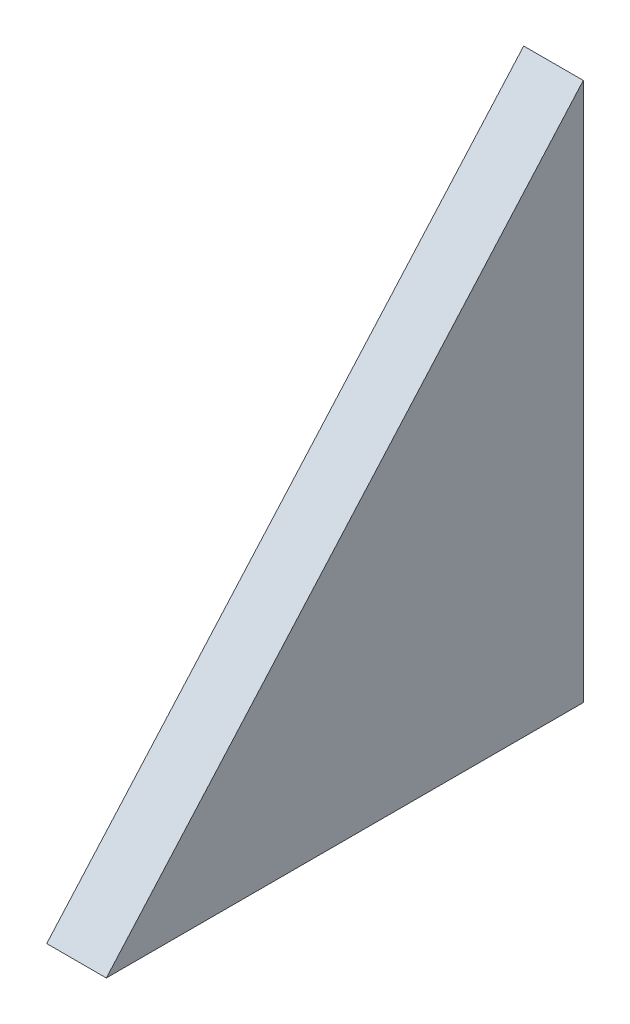
SolidWorks part; units mm, degrees
ref_plane "Alzado" through (0, 0, 0) normal (0, 0, 1) x (1, 0, 0)
ref_plane "Planta" through (0, 0, 0) normal (0, 1, 0) x (1, 0, 0)
ref_plane "Vista lateral" through (0, 0, 0) normal (1, 0, 0) x (0, 0, -1)
sketch "Croquis1" plane through (0, 0, 0) normal (1, 0, 0) x (0, 0, -1)
  line L1 (-32.0744, -36.234) -> (31.9256, -36.234)
  line L4 (31.9256, -36.234) -> (31.9256, 36.066)
  line L5 (-32.0744, -36.234) -> (31.9256, 36.066) construction
  line L6 (0, 0) -> (31.9256, -36.234) construction
  line L9 (-32.0744, -36.234) -> (31.9256, 36.066)
  point P0 (0, 0)
  dimension "D1" = 64
  dimension "D2" = 72.3
extrude "Saliente-Extruir1" add sketch "Croquis1" along normal blind 8
